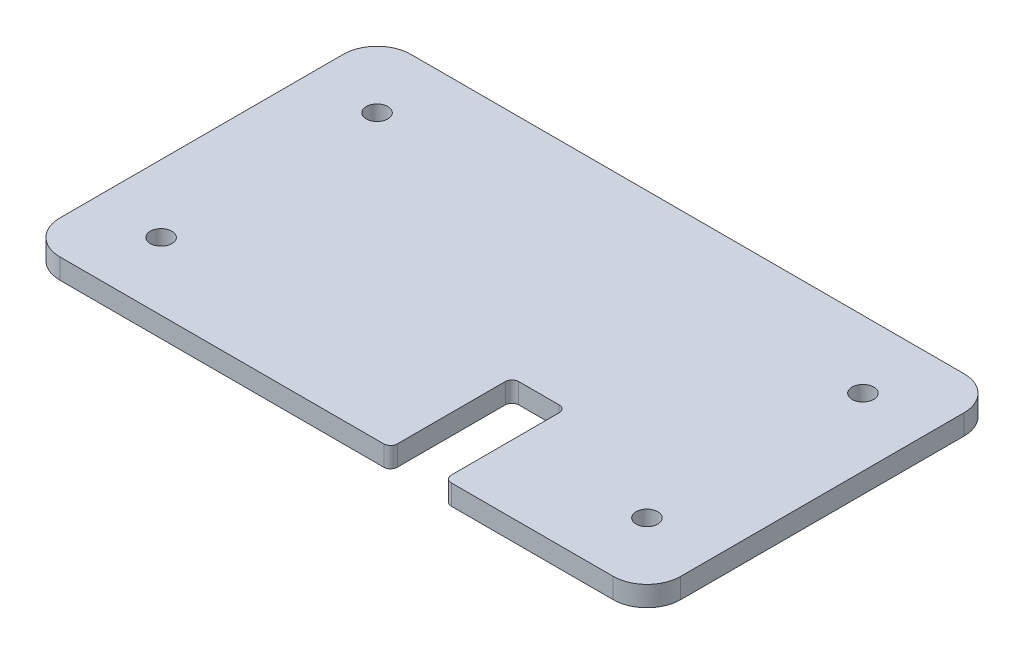
SolidWorks part; units mm, degrees
material "PVC 0.007 塑化"
ref_plane "前视基准面" through (0, 0, 0) normal (0, 0, 1) x (1, 0, 0)
ref_plane "上视基准面" through (0, 0, 0) normal (0, 1, 0) x (1, 0, 0)
ref_plane "右视基准面" through (0, 0, 0) normal (1, 0, 0) x (0, 0, -1)
other "Configuration Table"
sketch "草图1" plane through (0, 0, 0) normal (0, 1, 0) x (1, 0, 0)
  line L0 (8, -26) -> (8, -8)
  line L1 (-46, 26) -> (46, 26)
  line L2 (-46, 26) -> (-46, -26)
  line L3 (-46, -26) -> (8, -26)
  line L4 (46, 26) -> (46, -26)
  line L5 (-46, 26) -> (46, -26) construction
  line L6 (-46, -26) -> (46, 26) construction
  line L7 (-36, 16) -> (36, 16) construction
  line L8 (-36, 16) -> (-36, -16) construction
  line L9 (-36, -16) -> (36, -16) construction
  line L10 (36, 16) -> (36, -16) construction
  line L11 (-36, 16) -> (36, -16) construction
  line L12 (-36, -16) -> (36, 16) construction
  line L13 (8, -8) -> (16, -8)
  line L14 (16, -8) -> (16, -26)
  line L15 (16, -26) -> (46, -26)
  circle A0 centre (-36, 16) radius 1.6
  circle A1 centre (-36, -16) radius 1.6
  circle A2 centre (36, -16) radius 1.6
  circle A3 centre (36, 16) radius 1.6
  point P0 (0, 0)
  point P5 (0, 0)
  dimension "D5" = 3.2
  dimension "D1" = 52
  dimension "D2" = 92
  dimension "D3" = 32
  dimension "D4" = 72
  dimension "D6" = 18
  dimension "D7" = 8
  dimension "D8" = 20
extrude "凸台-拉伸1" add sketch "草图1" along normal blind 3
fillet "圆角1" radius 5 4 edges at (46, 1.5, -26) (-46, 1.5, -26) (-46, 1.5, 26) (46, 1.5, 26)
fillet "圆角2" radius 1 4 edges at (8, 1.5, 26) (16, 1.5, 26) (16, 1.5, 8) (8, 1.5, 8)
